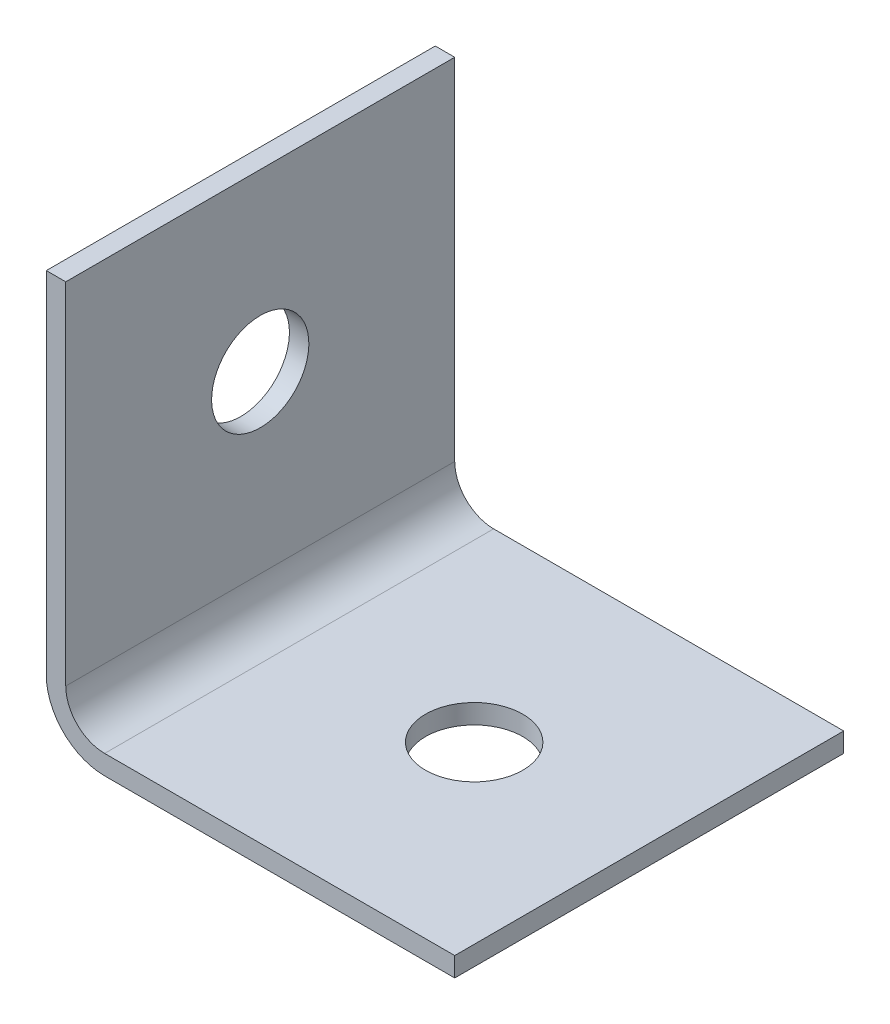
SolidWorks part; units mm, degrees
ref_plane "Front Plane" through (0, 0, 0) normal (0, 0, 1) x (1, 0, 0)
ref_plane "Top Plane" through (0, 0, 0) normal (0, 1, 0) x (1, 0, 0)
ref_plane "Right Plane" through (0, 0, 0) normal (1, 0, 0) x (0, 0, -1)
sketch "Sketch1" plane through (0, 0, 0) normal (0, 0, 1) x (1, 0, 0)
  line L0 (0, 0) -> (0, -20)
  line L1 (0, -20) -> (20, -20)
  dimension "D1" = 20
  dimension "D2" = 20
extrude "Extrude-Thin1" add sketch "Sketch1" along normal blind 20 thin
fillet "Fillet1" radius 3 1 edges at (-1, -21, 10)
fillet "Fillet3" radius 2 1 edges at (0, -20, 10)
sketch "Sketch3" plane through (0, 0, 0) normal (1, 0, 0) x (0, 0, -1)
  circle A0 centre (-10, -9) radius 2.5
extrude "Cut-Extrude1" cut sketch "Sketch3" against normal blind 10
sketch "Sketch4" plane through (0, -20, 0) normal (0, 1, 0) x (1, 0, 0)
  circle A0 centre (11, -10) radius 2.5
extrude "Cut-Extrude2" cut sketch "Sketch4" against normal blind 10
